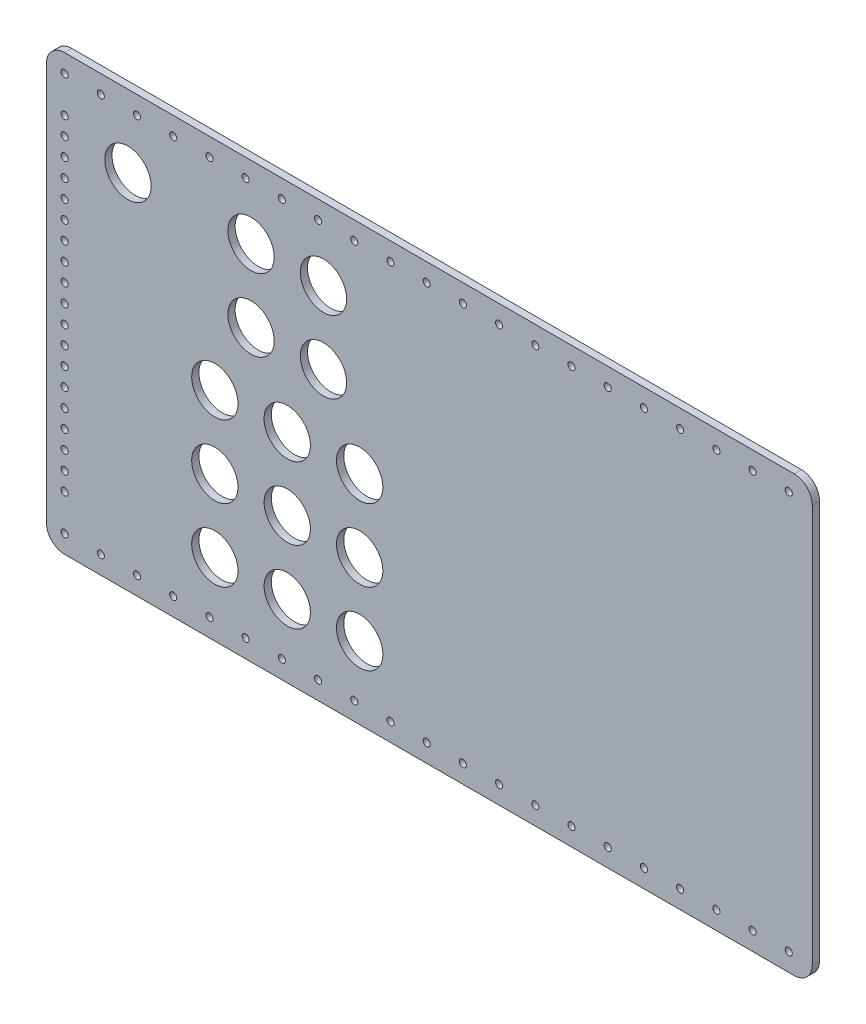
SolidWorks part; units mm, degrees
material "PC High Viscosity"
ref_plane "Front Plane" through (0, 0, 0) normal (0, 0, 1) x (1, 0, 0)
ref_plane "Top Plane" through (0, 0, 0) normal (0, 1, 0) x (1, 0, 0)
ref_plane "Right Plane" through (0, 0, 0) normal (1, 0, 0) x (0, 0, -1)
sketch "Sketch1" plane through (0, 0, 0) normal (0, 0, 1) x (1, 0, 0)
  line L1 (0, 0) -> (381, 0)
  line L2 (0, 0) -> (0, 304.8)
  line L3 (0, 304.8) -> (381, 304.8)
  line L4 (381, 0) -> (381, 304.8)
  dimension "D1" = 381
  dimension "D2" = 304.8
extrude "Boss-Extrude1" add sketch "Sketch1" along normal blind 5.08
sketch "Sketch2" plane through (0, 0, 0) normal (0, 0, -1) x (-1, 0, 0)
  line L1 (-381, 304.8) -> (0, 304.8) construction
  line L2 (-523.4473, 152.4) -> (65.789, 152.4) construction
  dimension "D4" = 152.4
sketch "Sketch3" plane through (0, 0, 0) normal (0, 0, -1) x (-1, 0, 0)
  line L0 (-247.65, 343.5749) -> (-247.65, -43.3065)
  line L1 (-381, 0) -> (-381, 304.8) construction
  line L2 (0, 0) -> (-381, 0) construction
  line L3 (-381, 304.8) -> (0, 304.8) construction
  line L4 (-368.3, 304.8) -> (-501.65, 304.8)
  line L5 (-368.3, 304.8) -> (-368.3, 0)
  line L6 (-368.3, 0) -> (-501.65, 0)
  line L7 (-501.65, 304.8) -> (-501.65, 0)
  line L8 (0, 304.8) -> (0, 0) construction
  line L9 (-2.5625, 304.8) -> (35.5375, 304.8)
  line L10 (-2.5625, 304.8) -> (-2.5625, 0)
  line L11 (-2.5625, 0) -> (35.5375, 0)
  line L12 (35.5375, 304.8) -> (35.5375, 0)
  circle A0 centre (-158.75, 254) radius 16.25
  circle A1 centre (-107.95, 254) radius 16.25
  circle A2 centre (-158.75, 203.2) radius 16.25
  circle A4 centre (-107.95, 203.2) radius 16.25
  circle A5 centre (-133.35, 152.4) radius 16.25
  circle A6 centre (-82.55, 152.4) radius 16.25
  circle A7 centre (-184.15, 152.4) radius 16.25
  circle A8 centre (-133.35, 101.6) radius 16.25
  circle A9 centre (-82.55, 101.6) radius 16.25
  circle A10 centre (-184.15, 101.6) radius 16.25
  circle A11 centre (-133.35, 50.8) radius 16.25
  circle A12 centre (-82.55, 50.8) radius 16.25
  circle A13 centre (-184.15, 50.8) radius 16.25
  circle A14 centre (-21.59, 254) radius 16.256
  dimension "D2" = 32.5
  dimension "D3" = 63.5
  dimension "D4" = 50.8
  dimension "D5" = 50.8
  dimension "D6" = 50.8
  dimension "D7" = 50.8
  dimension "D8" = 50.8
  dimension "D9" = 50.8
  dimension "D10" = 25.4
  dimension "D11" = 50.8
  dimension "D12" = 50.8
  dimension "D13" = 32.512
  dimension "D14" = 86.36
  dimension "D1" = 133.35
  dimension "D15" = 50.8
  dimension "D16" = 254
  dimension "D17" = 12.7
  dimension "D18" = 38.1
  dimension "D19" = 2.5625
  dimension "D20" = 304.8
extrude "Cut-Extrude2" cut sketch "Sketch3" against normal through all contours A0 | A1 | A14 | A2 | A4 | A7 | A5 | A6 | A10 | A8 | A9 | A13 | A11 | A12
sketch "Sketch4" plane through (0, 0, 0) normal (0, 0, -1) x (-1, 0, 0)
  line L1 (-501.65, 304.8) -> (-368.3, 304.8)
  line L2 (-501.65, 304.8) -> (-501.65, 0)
  line L3 (-501.65, 0) -> (-368.3, 0)
  line L4 (-368.3, 304.8) -> (-368.3, 0)
  line L5 (-2.5625, 304.8) -> (35.5375, 304.8)
  line L6 (-2.5625, 304.8) -> (-2.5625, 0)
  line L7 (-2.5625, 0) -> (35.5375, 0)
  line L8 (35.5375, 304.8) -> (35.5375, 0)
extrude "Boss-Extrude2" add sketch "Sketch4" against normal through all contours L2 L1 L4 L3 | L6 L5 L8 L7
sketch "Sketch5" plane through (0, 0, 0) normal (0, 0, -1) x (-1, 0, 0)
  line L0 (35.5375, 304.8) -> (35.5375, 0) construction
  line L1 (-501.65, 304.8) -> (35.5375, 304.8) construction
  line L2 (22.8375, 292.1) -> (22.8375, 266.7) construction
  line L3 (22.8375, 254) -> (22.8375, 228.6) construction
  line L4 (22.8375, 292.1) -> (-2.5625, 292.1) construction
  line L5 (22.8375, 12.7) -> (-2.5625, 12.7) construction
  circle A0 centre (22.8375, 292.1) radius 2.4892
  circle A1 centre (22.8375, 266.7) radius 2.4892
  circle A2 centre (22.8375, 241.3) radius 2.4892
  circle A3 centre (22.8375, 215.9) radius 2.4892
  circle A4 centre (22.8375, 190.5) radius 2.4892
  circle A5 centre (22.8375, 165.1) radius 2.4892
  circle A6 centre (22.8375, 139.7) radius 2.4892
  circle A7 centre (22.8375, 114.3) radius 2.4892
  circle A8 centre (22.8375, 88.9) radius 2.4892
  circle A9 centre (22.8375, 63.5) radius 2.4892
  circle A10 centre (22.8375, 38.1) radius 2.4892
  circle A11 centre (22.8375, 12.7) radius 2.4892
  circle A12 centre (22.8375, 254) radius 2.4892
  circle A13 centre (22.8375, 228.6) radius 2.4892
  circle A14 centre (22.8375, 203.2) radius 2.4892
  circle A15 centre (22.8375, 177.8) radius 2.4892
  circle A16 centre (22.8375, 152.4) radius 2.4892
  circle A17 centre (22.8375, 127) radius 2.4892
  circle A18 centre (22.8375, 101.6) radius 2.4892
  circle A19 centre (22.8375, 76.2) radius 2.4892
  circle A20 centre (22.8375, 50.8) radius 2.4892
  circle A21 centre (-2.5625, 292.1) radius 2.4892
  circle A22 centre (-27.9625, 292.1) radius 2.4892
  circle A23 centre (-53.3625, 292.1) radius 2.4892
  circle A24 centre (-78.7625, 292.1) radius 2.4892
  circle A25 centre (-104.1625, 292.1) radius 2.4892
  circle A26 centre (-129.5625, 292.1) radius 2.4892
  circle A27 centre (-154.9625, 292.1) radius 2.4892
  circle A28 centre (-180.3625, 292.1) radius 2.4892
  circle A29 centre (-205.7625, 292.1) radius 2.4892
  circle A30 centre (-231.1625, 292.1) radius 2.4892
  circle A31 centre (-256.5625, 292.1) radius 2.4892
  circle A32 centre (-281.9625, 292.1) radius 2.4892
  circle A33 centre (-307.3625, 292.1) radius 2.4892
  circle A34 centre (-332.7625, 292.1) radius 2.4892
  circle A35 centre (-358.1625, 292.1) radius 2.4892
  circle A36 centre (-383.5625, 292.1) radius 2.4892
  circle A37 centre (-408.9625, 292.1) radius 2.4892
  circle A38 centre (-434.3625, 292.1) radius 2.4892
  circle A39 centre (-459.7625, 292.1) radius 2.4892
  circle A40 centre (-485.1625, 292.1) radius 2.4892
  circle A41 centre (-2.5625, 12.7) radius 2.4892
  circle A42 centre (-27.9625, 12.7) radius 2.4892
  circle A43 centre (-53.3625, 12.7) radius 2.4892
  circle A44 centre (-78.7625, 12.7) radius 2.4892
  circle A45 centre (-104.1625, 12.7) radius 2.4892
  circle A46 centre (-129.5625, 12.7) radius 2.4892
  circle A47 centre (-154.9625, 12.7) radius 2.4892
  circle A48 centre (-180.3625, 12.7) radius 2.4892
  circle A49 centre (-205.7625, 12.7) radius 2.4892
  circle A50 centre (-231.1625, 12.7) radius 2.4892
  circle A51 centre (-256.5625, 12.7) radius 2.4892
  circle A52 centre (-281.9625, 12.7) radius 2.4892
  circle A53 centre (-307.3625, 12.7) radius 2.4892
  circle A54 centre (-332.7625, 12.7) radius 2.4892
  circle A55 centre (-358.1625, 12.7) radius 2.4892
  circle A56 centre (-383.5625, 12.7) radius 2.4892
  circle A57 centre (-408.9625, 12.7) radius 2.4892
  circle A58 centre (-434.3625, 12.7) radius 2.4892
  circle A59 centre (-459.7625, 12.7) radius 2.4892
  circle A60 centre (-485.1625, 12.7) radius 2.4892
  dimension "D1" = 4.9784
  dimension "D2" = 12.7
  dimension "D3" = 12.7
  dimension "D6" = 12.7
  dimension "D5" = 25.4
  dimension "D8" = 25.4
  dimension "D10" = 25.4
  dimension "D12" = 25.4
  dimension "D4" = 12
  dimension "D7" = 9
  dimension "D9" = 21
  dimension "D11" = 21
extrude "Cut-Extrude3" cut sketch "Sketch5" against normal through all
fillet "Fillet1" radius 12.7 4 edges at (501.65, 0, 2.54) (-35.5375, 0, 2.54) (-35.5375, 304.8, 2.54) (501.65, 304.8, 2.54)
